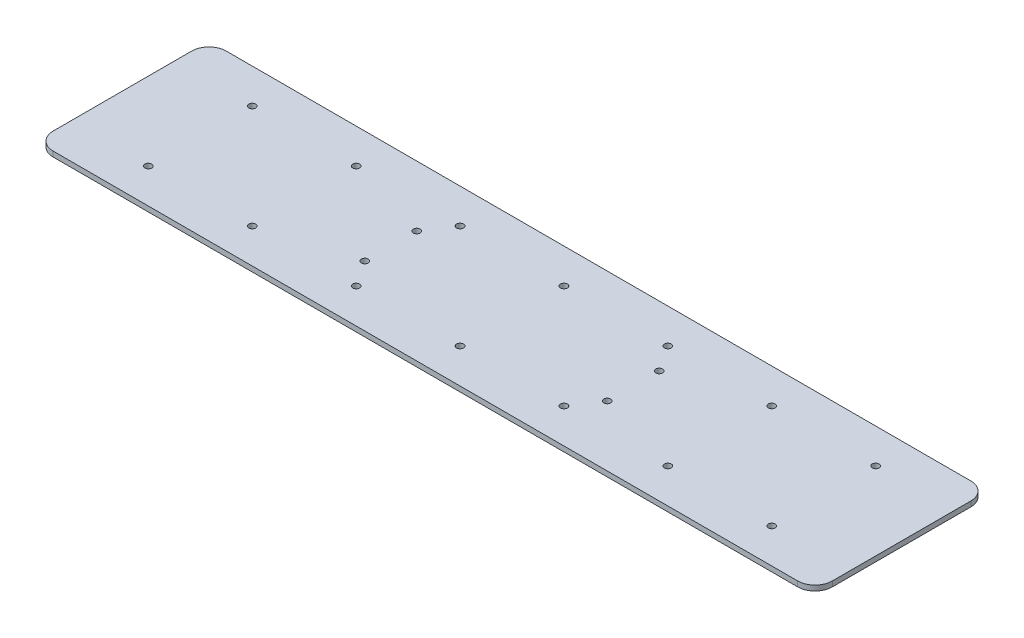
SolidWorks part; units mm, degrees
ref_plane "前视基准面" through (0, 0, 0) normal (0, 0, 1) x (1, 0, 0)
ref_plane "上视基准面" through (0, 0, 0) normal (0, 1, 0) x (1, 0, 0)
ref_plane "右视基准面" through (0, 0, 0) normal (1, 0, 0) x (0, 0, -1)
sketch "草图1" plane through (0, 0, 0) normal (0, 1, 0) x (1, 0, 0)
  line L1 (-215, 50) -> (215, 50)
  line L2 (-225, 40) -> (-225, -40)
  line L3 (-215, -50) -> (215, -50)
  line L4 (225, 40) -> (225, -40)
  line L5 (-225, 50) -> (225, -50) construction
  line L6 (-225, -50) -> (225, 50) construction
  arc A0 (215, -50) -> (225, -40) centre (215, -40) ccw
  arc A1 (225, 40) -> (215, 50) centre (215, 40) ccw
  arc A2 (-225, -40) -> (-215, -50) centre (-215, -40) ccw
  arc A3 (-225, 40) -> (-215, 50) centre (-215, 40) cw
  point P0 (0, 0)
  dimension "D1" = 10
extrude "凸台-拉伸1" add sketch "草图1" along normal blind 3
sketch "草图2" plane through (0, 3, 0) normal (0, 1, 0) x (1, 0, 0)
  circle A0 centre (-180, -30) radius 2
  circle A1 centre (-120, -30) radius 2
  circle A2 centre (-60, -30) radius 2
  circle A3 centre (0, -30) radius 2
  circle A4 centre (60, -30) radius 2
  circle A5 centre (120, -30) radius 2
  circle A6 centre (180, -30) radius 2
  dimension "D1" = 7
extrude "切除-拉伸1" cut sketch "草图2" against normal through all
sketch "草图3" plane through (0, 3, 0) normal (0, 1, 0) x (1, 0, 0)
  circle A0 centre (-180, 30) radius 2
  circle A1 centre (-120, 30) radius 2
  circle A2 centre (-60, 30) radius 2
  circle A3 centre (0, 30) radius 2
  circle A4 centre (60, 30) radius 2
  circle A5 centre (120, 30) radius 2
  circle A6 centre (180, 30) radius 2
  dimension "D1" = 7
extrude "切除-拉伸2" cut sketch "草图3" against normal through all
sketch "草图4" plane through (0, 3, 0) normal (0, 1, 0) x (1, 0, 0)
  circle A0 centre (-70, 15) radius 2
  circle A1 centre (70, 15) radius 2
  circle A2 centre (-70, -15) radius 2
  circle A4 centre (70, -15) radius 2
  dimension "D1" = 2
  dimension "D2" = 2
extrude "切除-拉伸3" cut sketch "草图4" against normal through all
